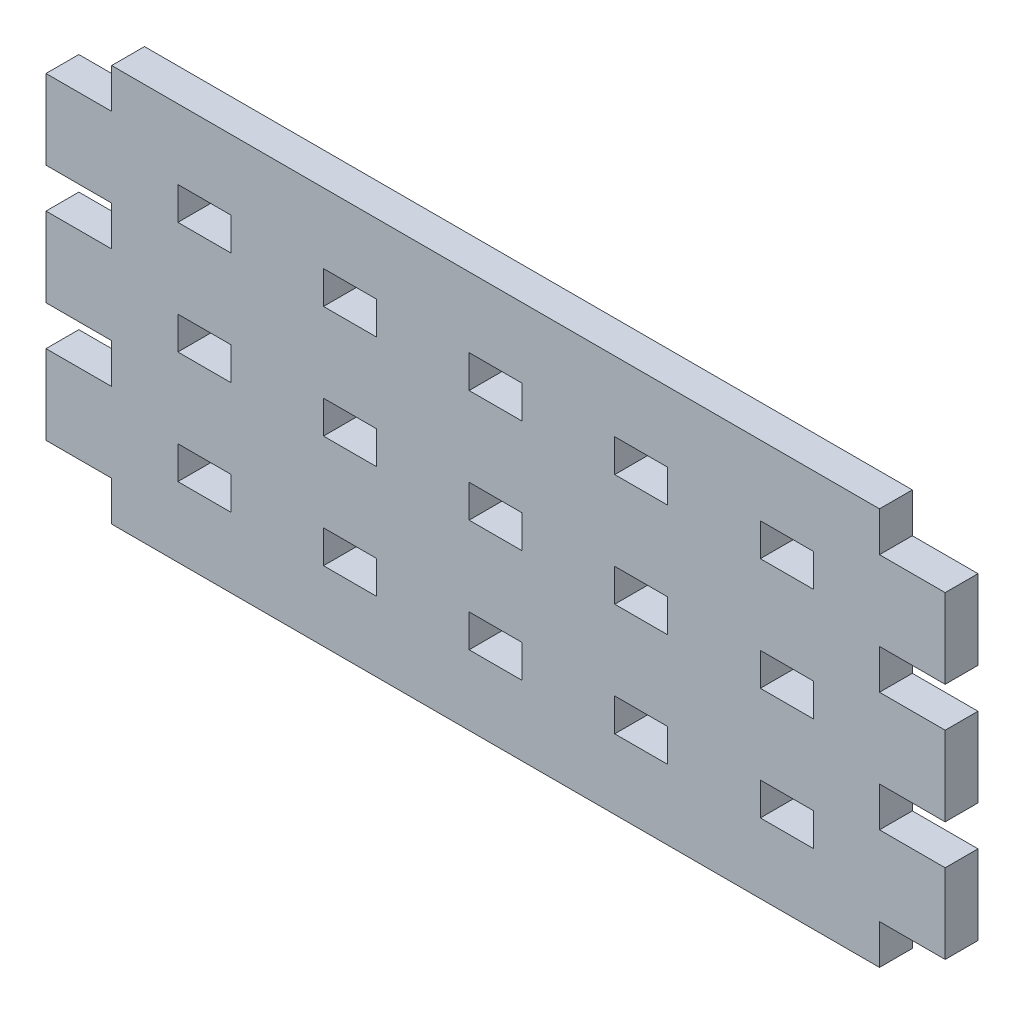
SolidWorks part; units mm, degrees
ref_plane "Front Plane" through (0, 0, 0) normal (0, 0, 1) x (1, 0, 0)
ref_plane "Top Plane" through (0, 0, 0) normal (0, 1, 0) x (1, 0, 0)
ref_plane "Right Plane" through (0, 0, 0) normal (1, 0, 0) x (0, 0, -1)
sketch "Model" plane through (0, 0, 0) normal (0, 0, 1) x (1, 0, 0)
  line L0 (-24.8, 75) -> (314.8, 75) construction
  line L88 (0, 135) -> (0, 150)
  line L89 (0, 0) -> (290, 0)
  line L90 (0, 0) -> (0, 15)
  line L91 (0, 150) -> (290, 150)
  line L92 (290, 0) -> (290, 15)
  line L93 (0, 135) -> (-24.8, 135)
  line L94 (0, 90) -> (0, 105)
  line L95 (0, 105) -> (-24.8, 105)
  line L96 (-24.8, 135) -> (-24.8, 105)
  line L97 (0, 90) -> (-24.8, 90)
  line L98 (0, 45) -> (0, 60)
  line L99 (0, 60) -> (-24.8, 60)
  line L100 (-24.8, 90) -> (-24.8, 60)
  line L101 (0, 45) -> (-24.8, 45)
  line L102 (145, 0) -> (145, 150) construction
  line L103 (0, 15) -> (-24.8, 15)
  line L104 (-24.8, 45) -> (-24.8, 15)
  line L105 (314.8, 45) -> (314.8, 15)
  line L106 (290, 15) -> (314.8, 15)
  line L107 (290, 45) -> (314.8, 45)
  line L108 (314.8, 90) -> (314.8, 60)
  line L109 (290, 60) -> (314.8, 60)
  line L110 (290, 90) -> (314.8, 90)
  line L111 (314.8, 135) -> (314.8, 105)
  line L112 (290, 105) -> (314.8, 105)
  line L113 (290, 135) -> (314.8, 135)
  line L114 (290, 135) -> (290, 150)
  line L115 (290, 90) -> (290, 105)
  line L116 (290, 45) -> (290, 60)
  line L117 (190, 111.2) -> (210, 111.2)
  line L118 (135, 111.2) -> (155, 111.2)
  line L119 (135, 111.2) -> (135, 123.6)
  line L120 (135, 123.6) -> (155, 123.6)
  line L121 (155, 111.2) -> (155, 123.6)
  line L122 (135, 111.2) -> (155, 123.6) construction
  line L123 (135, 123.6) -> (155, 111.2) construction
  line L124 (190, 111.2) -> (190, 123.6)
  line L125 (190, 123.6) -> (210, 123.6)
  line L126 (210, 111.2) -> (210, 123.6)
  line L127 (190, 111.2) -> (210, 123.6) construction
  line L128 (190, 123.6) -> (210, 111.2) construction
  line L129 (245, 111.2) -> (265, 111.2)
  line L130 (245, 111.2) -> (245, 123.6)
  line L131 (245, 123.6) -> (265, 123.6)
  line L132 (265, 111.2) -> (265, 123.6)
  line L133 (245, 111.2) -> (265, 123.6) construction
  line L134 (245, 123.6) -> (265, 111.2) construction
  line L135 (190, 68.8) -> (210, 68.8)
  line L136 (190, 68.8) -> (190, 81.2)
  line L137 (190, 81.2) -> (210, 81.2)
  line L138 (210, 68.8) -> (210, 81.2)
  line L139 (190, 68.8) -> (210, 81.2) construction
  line L140 (190, 81.2) -> (210, 68.8) construction
  line L141 (245, 68.8) -> (265, 68.8)
  line L142 (245, 68.8) -> (245, 81.2)
  line L143 (245, 81.2) -> (265, 81.2)
  line L144 (265, 68.8) -> (265, 81.2)
  line L145 (245, 68.8) -> (265, 81.2) construction
  line L146 (245, 81.2) -> (265, 68.8) construction
  line L147 (190, 26.4) -> (210, 26.4)
  line L148 (190, 26.4) -> (190, 38.8)
  line L149 (190, 38.8) -> (210, 38.8)
  line L150 (210, 26.4) -> (210, 38.8)
  line L151 (190, 26.4) -> (210, 38.8) construction
  line L152 (190, 38.8) -> (210, 26.4) construction
  line L153 (245, 26.4) -> (265, 26.4)
  line L154 (245, 26.4) -> (245, 38.8)
  line L155 (245, 38.8) -> (265, 38.8)
  line L156 (265, 26.4) -> (265, 38.8)
  line L157 (245, 26.4) -> (265, 38.8) construction
  line L158 (245, 38.8) -> (265, 26.4) construction
  line L159 (135, 68.8) -> (155, 68.8)
  line L160 (135, 68.8) -> (135, 81.2)
  line L161 (135, 81.2) -> (155, 81.2)
  line L162 (155, 68.8) -> (155, 81.2)
  line L163 (135, 68.8) -> (155, 81.2) construction
  line L164 (135, 81.2) -> (155, 68.8) construction
  line L165 (135, 26.4) -> (155, 26.4)
  line L166 (135, 26.4) -> (135, 38.8)
  line L167 (135, 38.8) -> (155, 38.8)
  line L168 (155, 26.4) -> (155, 38.8)
  line L169 (135, 26.4) -> (155, 38.8) construction
  line L170 (135, 38.8) -> (155, 26.4) construction
  line L171 (80, 111.2) -> (100, 111.2)
  line L172 (80, 111.2) -> (80, 123.6)
  line L173 (80, 123.6) -> (100, 123.6)
  line L174 (100, 111.2) -> (100, 123.6)
  line L175 (80, 111.2) -> (100, 123.6) construction
  line L176 (80, 123.6) -> (100, 111.2) construction
  line L177 (25, 111.2) -> (45, 111.2)
  line L178 (25, 111.2) -> (25, 123.6)
  line L179 (25, 123.6) -> (45, 123.6)
  line L180 (45, 111.2) -> (45, 123.6)
  line L181 (25, 111.2) -> (45, 123.6) construction
  line L182 (25, 123.6) -> (45, 111.2) construction
  line L183 (80, 68.8) -> (100, 68.8)
  line L184 (80, 68.8) -> (80, 81.2)
  line L185 (80, 81.2) -> (100, 81.2)
  line L186 (100, 68.8) -> (100, 81.2)
  line L187 (80, 68.8) -> (100, 81.2) construction
  line L188 (80, 81.2) -> (100, 68.8) construction
  line L189 (25, 68.8) -> (45, 68.8)
  line L190 (25, 68.8) -> (25, 81.2)
  line L191 (25, 81.2) -> (45, 81.2)
  line L192 (45, 68.8) -> (45, 81.2)
  line L193 (25, 68.8) -> (45, 81.2) construction
  line L194 (25, 81.2) -> (45, 68.8) construction
  line L195 (80, 26.4) -> (100, 26.4)
  line L196 (80, 26.4) -> (80, 38.8)
  line L197 (80, 38.8) -> (100, 38.8)
  line L198 (100, 26.4) -> (100, 38.8)
  line L199 (80, 26.4) -> (100, 38.8) construction
  line L200 (80, 38.8) -> (100, 26.4) construction
  line L201 (25, 26.4) -> (45, 26.4)
  line L202 (25, 26.4) -> (25, 38.8)
  line L203 (25, 38.8) -> (45, 38.8)
  line L204 (45, 26.4) -> (45, 38.8)
  line L205 (25, 26.4) -> (45, 38.8) construction
  line L206 (25, 38.8) -> (45, 26.4) construction
  line L207 (135, 68.8) -> (155, 68.8) [skipped]
  line L208 (135, 68.8) -> (135, 81.2) [skipped]
  line L209 (135, 81.2) -> (155, 81.2) [skipped]
  line L210 (155, 68.8) -> (155, 81.2) [skipped]
  line L211 (135, 68.8) -> (155, 81.2) construction
  line L212 (135, 81.2) -> (155, 68.8) construction
  line L213 (135, 26.4) -> (155, 26.4) [skipped]
  line L214 (135, 26.4) -> (135, 38.8) [skipped]
  line L215 (135, 38.8) -> (155, 38.8) [skipped]
  line L216 (155, 26.4) -> (155, 38.8) [skipped]
  line L217 (135, 26.4) -> (155, 38.8) construction
  line L218 (135, 38.8) -> (155, 26.4) construction
  point P30 (145, 117.4)
  point P37 (145, 75)
  point P38 (200, 117.4)
  point P43 (255, 117.4)
  point P48 (200, 75)
  point P53 (255, 75)
  point P58 (200, 32.6)
  point P63 (255, 32.6)
  point P68 (145, 75)
  point P73 (145, 32.6)
  point P78 (90, 117.4)
  point P83 (35, 117.4)
  point P88 (90, 75)
  point P93 (35, 75)
  point P98 (90, 32.6)
  point P103 (35, 32.6)
  point P197 (145, 75)
  point P202 (145, 32.6)
  dimension "D2" = 290
  dimension "D4" = 150
  dimension "D6" = 24.8
  dimension "D8" = 30
  dimension "D13" = 12.4
  dimension "D15" = 20
  dimension "D19" = 35
  dimension "D24" = 35
  dimension "D26" = 30
  dimension "D10" = 3
  dimension "D11" = 3
  dimension "D22" = 3
  dimension "D23" = 3
extrude "Boss-Extrude1" add sketch "Model" along normal blind 12.4
equation "\"tab-width-large\"= 30mm ' Width of the large version of the Tab"
equation "\"tab-width-small\"= 20mm ' Width of the small version of the Tab"
equation "\"baseplate-width\"= 290mm"
equation "\"material-thickness\"= 12.4mm"
equation "\"D6@Model\"=\"material-thickness\" *2"
equation "\"D13@Model\"=\"material-thickness\""
equation "\"D1@Boss-Extrude1\" = \"material-thickness\""
equation "\"D2@Model\"=\"baseplate-width\""
equation "\"D8@Model\"=\"tab-width-large\""
equation "\"D15@Model\"=\"tab-width-small\""
